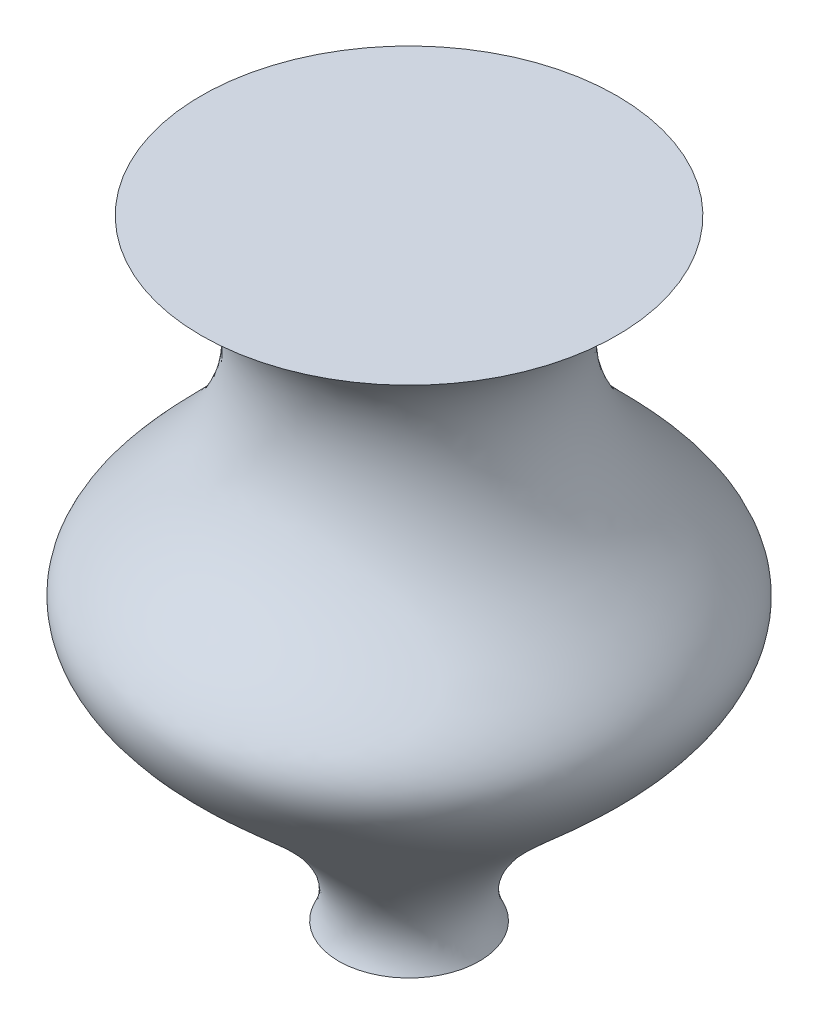
SolidWorks part; units mm, degrees
ref_plane "前视基准面" through (0, 0, 0) normal (0, 0, 1) x (1, 0, 0)
ref_plane "上视基准面" through (0, 0, 0) normal (0, 1, 0) x (1, 0, 0)
ref_plane "右视基准面" through (0, 0, 0) normal (1, 0, 0) x (0, 0, -1)
other "Configuration Table"
sketch "草图3" plane through (0, 0, 0) normal (0, 0, 1) x (1, 0, 0)
  line L0 (-4.4431, 15.6274) -> (-1.04, 15.6274)
  line L1 (-1.04, 15.6274) -> (-1.04, 5.6274)
  line L2 (-1.04, 5.6274) -> (-2.1918, 5.6274)
  spline S0 degree 3 poles (-4.4431, 15.6274) (-2.9702, 15.0365) (-2.8717, 12.4139) (-7.1661, 9.641) (-1.3424, 7.1998) (-2.1918, 5.6274) knots 0 0 0 0 0.328646 0.529079 1 1 1 1
  dimension "D1" = 10
revolve "旋转1" add sketch "草图3" angle 360 about L1
